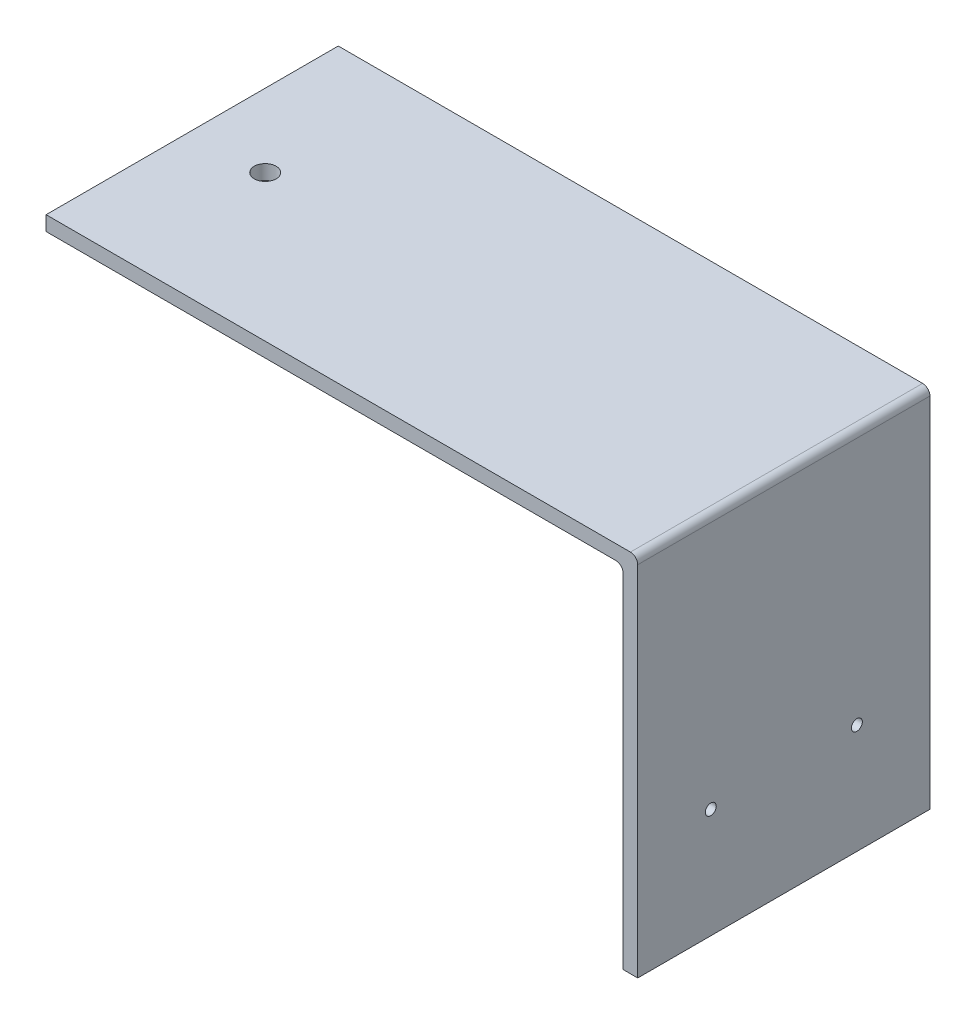
SolidWorks part; units mm, degrees
ref_plane "Front Plane" through (0, 0, 0) normal (0, 0, 1) x (1, 0, 0)
ref_plane "Top Plane" through (0, 0, 0) normal (0, 1, 0) x (1, 0, 0)
ref_plane "Right Plane" through (0, 0, 0) normal (1, 0, 0) x (0, 0, -1)
sketch "Sketch1" plane through (0, 0, 0) normal (0, 1, 0) x (1, 0, 0)
  line L1 (0, 0) -> (80, 0)
  line L2 (0, 0) -> (0, 40)
  line L3 (0, 40) -> (80, 40)
  line L4 (80, 0) -> (80, 40)
  circle A0 centre (10, 20) radius 1.5
  dimension "D3" = 10
  dimension "D4" = 20
  dimension "D1" = 40
  dimension "D2" = 80
extrude "Boss-Extrude1" add sketch "Sketch1" along normal blind 2
sketch "Sketch2" plane through (0, 2, 0) normal (0, 1, 0) x (1, 0, 0)
  line L0 (80, 40) -> (0, 40) construction
  line L1 (80, 0) -> (79, 0)
  line L2 (80, 0) -> (80, 40)
  line L3 (80, 40) -> (79, 40)
  line L4 (79, 0) -> (79, 40)
  line L6 (80, 0) -> (81, 0)
  line L7 (80, 0) -> (80, 40)
  line L8 (80, 40) -> (81, 40)
  line L9 (81, 0) -> (81, 40)
  line M2 (0, 0) -> (80, 0)
  line M3 (80, 0) -> (80, 40)
  line M4 (80, 40) -> (0, 40)
  dimension "D1" = 1
  dimension "D2" = 1
extrude "Boss-Extrude2" add sketch "Sketch2" against normal blind 50 contours L4 M2 M3 M4 | L6 L9 L8 M3
sketch "Sketch3" plane through (79, 0, 0) normal (-1, 0, 0) x (0, 0, 1)
  line L0 (-40, -48) -> (-40, 0) construction
  line L1 (0, -48) -> (-40, -48) construction
  line L2 (0, -48) -> (0, 0) construction
  circle A0 centre (-30, -33) radius 0.75
  circle A1 centre (-10, -33) radius 0.75
  dimension "D1" = 1.5
  dimension "D2" = 1.5
  dimension "D3" = 10
  dimension "D4" = 15
  dimension "D5" = 10
  dimension "D6" = 15
extrude "Cut-Extrude1" cut sketch "Sketch3" against normal blind 70
fillet "Fillet1" radius 1 2 edges at (79, 0, -20) (81, 2, -20)
